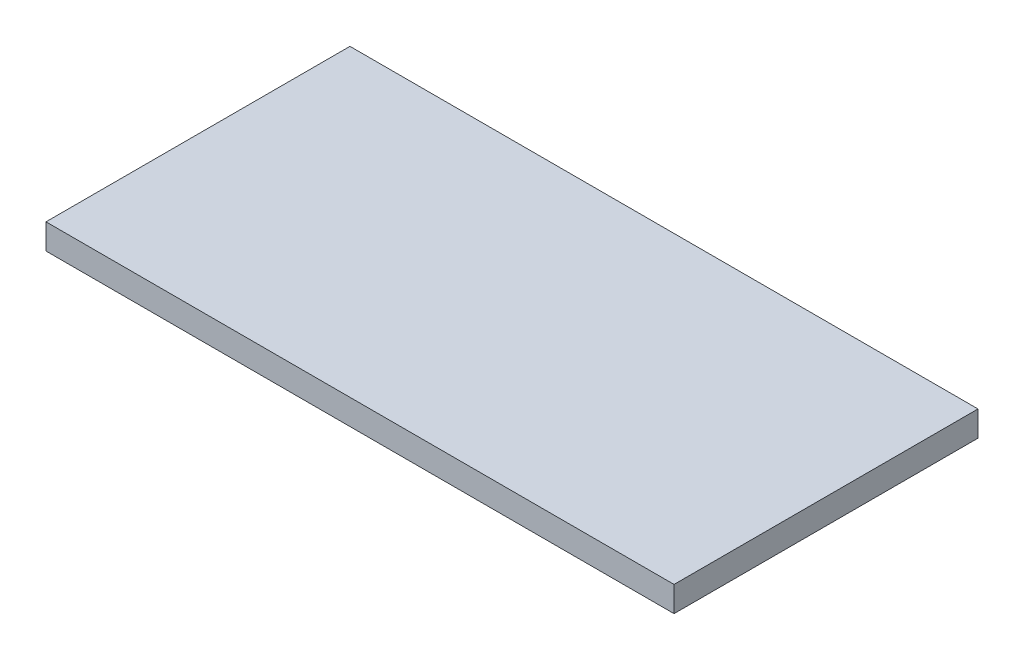
SolidWorks part; units mm, degrees
material "Plain Carbon Steel"
ref_plane "Front Plane" through (0, 0, 0) normal (0, 0, 1) x (1, 0, 0)
ref_plane "Top Plane" through (0, 0, 0) normal (0, 1, 0) x (1, 0, 0)
ref_plane "Right Plane" through (0, 0, 0) normal (1, 0, 0) x (0, 0, -1)
sketch "Sketch1" plane through (0, 0, 0) normal (0, 1, 0) x (1, 0, 0)
  line L1 (0, 0) -> (124, 0)
  line L2 (0, 0) -> (0, -60.01)
  line L3 (0, -60.01) -> (124, -60.01)
  line L4 (124, 0) -> (124, -60.01)
  dimension "D1" = 124
  dimension "D2" = 60.01
extrude "Boss-Extrude1" add sketch "Sketch1" along normal blind 5
